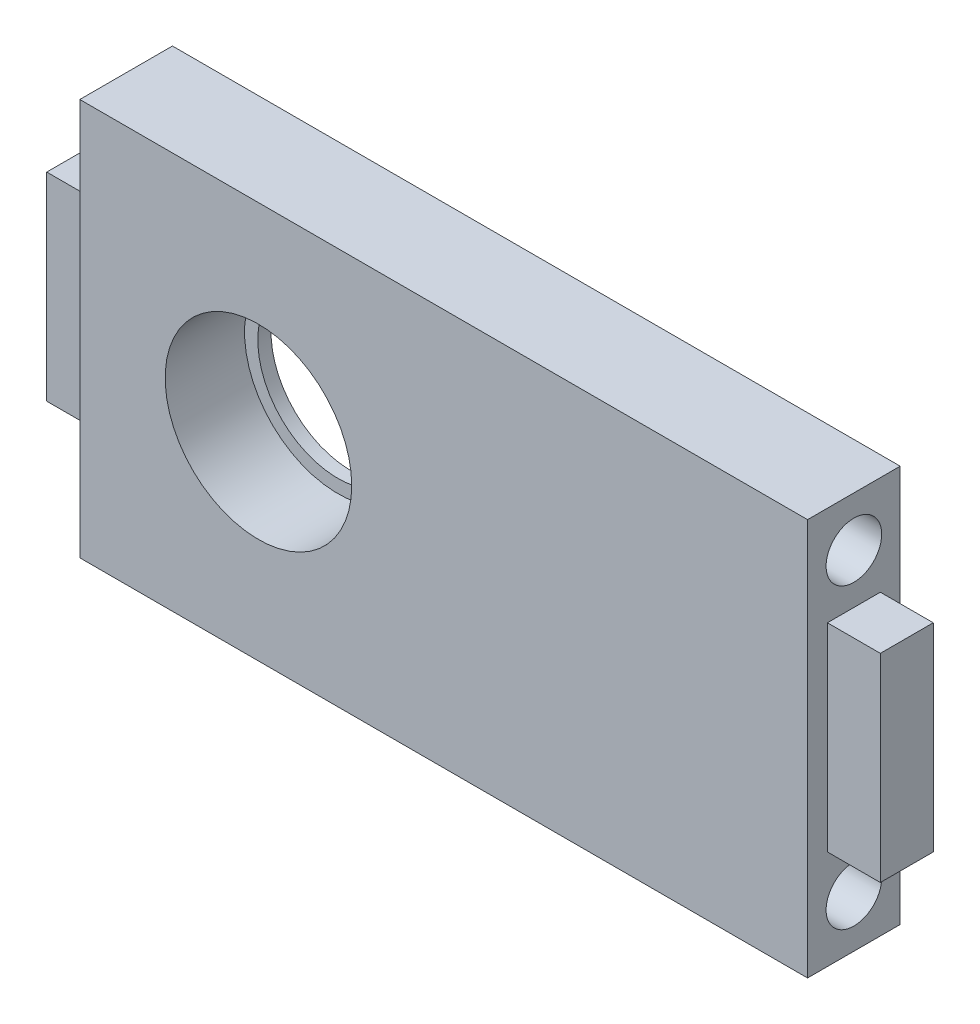
SolidWorks part; units mm, degrees
ref_plane "Спереди" through (0, 0, 0) normal (0, 0, 1) x (1, 0, 0)
ref_plane "Сверху" through (0, 0, 0) normal (0, 1, 0) x (1, 0, 0)
ref_plane "Справа" through (0, 0, 0) normal (1, 0, 0) x (0, 0, -1)
sketch "Эскиз1" plane through (0, 0, 0) normal (0, 0, 1) x (1, 0, 0)
  line L1 (-27.5, -15) -> (27.5, -15)
  line L2 (-27.5, -15) -> (-27.5, 15)
  line L3 (-27.5, 15) -> (27.5, 15)
  line L4 (27.5, -15) -> (27.5, 15)
  line L5 (-27.5, -15) -> (27.5, 15) construction
  line L6 (-27.5, 15) -> (27.5, -15) construction
  circle A1 centre (-14, 0) radius 7.05
  point P10 (0, 0)
  dimension "D1" = 14.1
  dimension "D2" = 30
  dimension "D3" = 55
  dimension "D4" = 13.5
extrude "Бобышка-Вытянуть1" add sketch "Эскиз1" along normal blind 7
sketch "Эскиз2" plane through (0, 0, 0) normal (0, 0, 1) x (1, 0, 0)
  circle A4 centre (-14, 0) radius 7.05 construction
  circle A5 centre (-14, 0) radius 7.05
  circle A6 centre (-14, 0) radius 6.05
  dimension "D1" = 1
extrude "Бобышка-Вытянуть2" add sketch "Эскиз2" along normal blind 1
sketch "Эскиз3" plane through (0, 0, 0) normal (0, 0, 1) x (1, 0, 0)
  line L0 (27.5, -15) -> (27.5, 15) construction
  line L1 (27.5, 7.5) -> (31.5, 7.5)
  line L2 (27.5, 7.5) -> (27.5, -7.5)
  line L3 (27.5, -7.5) -> (31.5, -7.5)
  line L4 (31.5, 7.5) -> (31.5, -7.5)
  line L5 (0, -55) -> (0, 55) construction
  line L6 (-31.5, 7.5) -> (-31.5, -7.5)
  line L7 (-27.5, -7.5) -> (-31.5, -7.5)
  line L8 (-27.5, 7.5) -> (-27.5, -7.5)
  line L9 (-27.5, 7.5) -> (-31.5, 7.5)
  point P6 (31.5, 0)
  dimension "D1" = 4
  dimension "D2" = 15
extrude "Бобышка-Вытянуть3" add sketch "Эскиз3" along normal blind 4 from offset 1.5
sketch "Эскиз4" plane through (27.5, 0, 0) normal (1, 0, 0) x (0, 0, -1)
  line L0 (-7, 15) -> (0, 15) construction
  line L1 (0, 15) -> (0, 7.5) construction
  line L2 (55, 0) -> (-55, 0) construction
  line L3 (0, -15) -> (0, -7.5) construction
  circle A0 centre (-3.5, 11.25) radius 2.1
  circle A1 centre (-3.5, -11.25) radius 2.1
  point P2 (0, 11.25)
  point P5 (-3.5, 15)
  dimension "D1" = 4.2
extrude "Вырез-Вытянуть1" cut sketch "Эскиз4" against normal blind 6
mirror "Зеркальное отражение1" about plane through (0, 0, 0) normal (1, 0, 0) of "Вырез-Вытянуть1"
